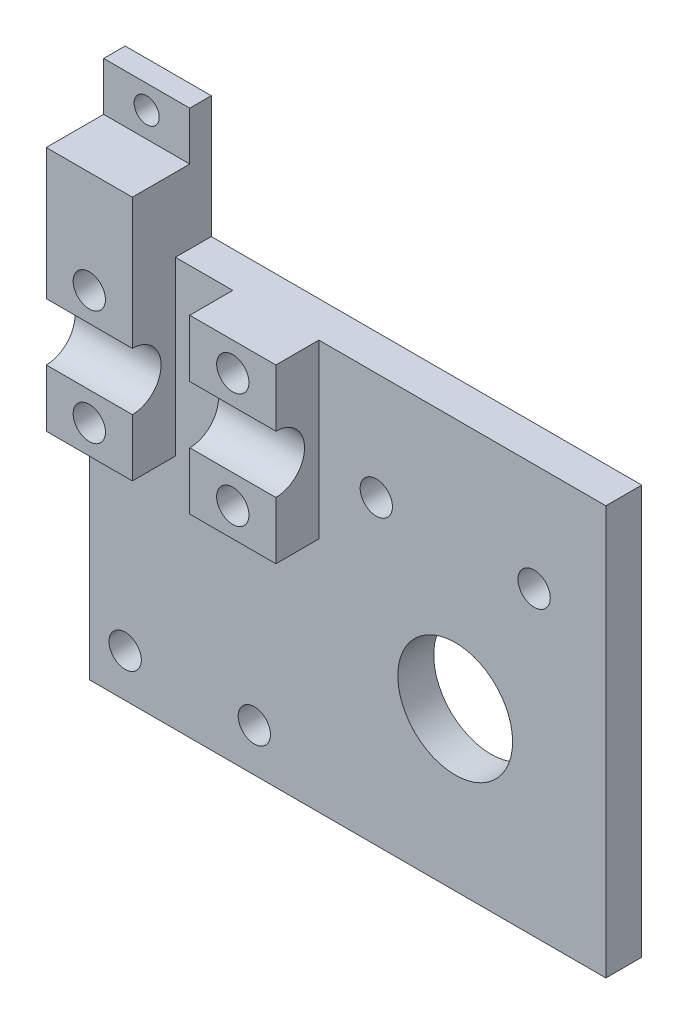
SolidWorks part; units mm, degrees
material "Printed PLA"
ref_plane "Front Plane" through (0, 0, 0) normal (0, 0, 1) x (1, 0, 0)
ref_plane "Top Plane" through (0, 0, 0) normal (0, 1, 0) x (1, 0, 0)
ref_plane "Right Plane" through (0, 0, 0) normal (1, 0, 0) x (0, 0, -1)
sketch "Sketch1" plane through (0, 0, 0) normal (0, 0, 1) x (1, 0, 0)
  line L0 (-16, 28.5) -> (56, -28.5) construction
  line L1 (-16, 28.5) -> (56, 28.5)
  line L2 (-16, 28.5) -> (-16, -28.5)
  line L3 (-16, -28.5) -> (56, -28.5)
  line L4 (56, 28.5) -> (56, -28.5)
  line L5 (20, 0) -> (0, 0) construction
  dimension "D1" = 72
  dimension "D2" = 57
  dimension "D3" = 20
extrude "Boss-Extrude1" add sketch "Sketch1" along normal blind 5
sketch "Sketch3" plane through (-16, 0, 0) normal (1, 0, 0) x (0, 0, -1)
  line L0 (-5, 28.5) -> (-11, 28.5)
  line L1 (-11, 28.5) -> (-11, 20.5)
  line L2 (-11, 12.5) -> (-11, 4.5)
  line L3 (-11, 4.5) -> (-5, 4.5)
  line L4 (-5, -28.5) -> (-5, 28.5) construction
  line L5 (-5, 4.5) -> (-5, 28.5)
  arc A0 (-11, 20.5) -> (-11, 12.5) centre (-11, 16.5) cw
  dimension "D1" = 4
  dimension "D2" = 8
  dimension "D3" = 6
extrude "Boss-Extrude2" add sketch "Sketch3" along normal blind 12
sketch "Sketch5" plane through (0, 0, 11) normal (0, 0, 1) x (1, 0, 0)
  line L0 (-10, 8.5) -> (-10, 24.5) construction
  line L1 (-10, 16.5) -> (-16, 16.5) construction
  line L2 (-16, 20.5) -> (-16, 12.5) construction
  line L3 (-10, 24.5) -> (-10, 28.5) construction
  line L4 (-4, 28.5) -> (-16, 28.5) construction
  circle A0 centre (-10, 24.5) radius 2.25
  circle A1 centre (-10, 8.5) radius 2.25
  dimension "D1" = 4.5
  dimension "D2" = 16
extrude "Cut-Extrude2" cut sketch "Sketch5" against normal through all
mirror "Mirror1" about plane through (0, 0, 0) normal (1, 0, 0) of "Cut-Extrude2", "Boss-Extrude2"
sketch "Sketch4" plane through (0, 0, 5) normal (0, 0, 1) x (1, 0, 0)
  line L0 (-16, -28.5) -> (56, -28.5) construction
  line L1 (35, -6.5) -> (35, -28.5) construction
  line L2 (19.5, -22) -> (19.5, 9) construction
  line L3 (19.5, 9) -> (50.5, 9) construction
  line L4 (50.5, 9) -> (50.5, -22) construction
  line L5 (50.5, -22) -> (19.5, -22) construction
  line L6 (19.5, -22) -> (50.5, 9) construction
  line L8 (56, -28.5) -> (56, 28.5) construction
  circle A0 centre (35, -6.5) radius 8
  circle A1 centre (19.5, 9) radius 1.75 construction
  circle A2 centre (50.5, 9) radius 1.75 construction
  circle A3 centre (50.5, -22) radius 1.75 construction
  circle A4 centre (19.5, -22) radius 1.75 construction
  dimension "D2" = 16
  dimension "D4" = 3.5
  dimension "D1" = 22
  dimension "D3" = 31
  dimension "D5" = 21
extrude "Cut-Extrude1" cut sketch "Sketch4" against normal through all
sketch "Sketch6" plane through (0, 0, 5) normal (0, 0, 1) x (1, 0, 0)
  line L0 (7, -22.5) -> (-11, -22.5) construction
  line L1 (-16, -28.5) -> (56, -28.5) construction
  line L2 (-2, -22.5) -> (-2, -17.3253) construction
  line L4 (-16, 4.5) -> (-16, -28.5) construction
  circle A0 centre (-11, -22.5) radius 2.25
  circle A1 centre (7, -22.5) radius 2.25
  dimension "D1" = 4.5
  dimension "D2" = 18
  dimension "D3" = 6
  dimension "D4" = 14
extrude "Cut-Extrude3" cut sketch "Sketch6" against normal through all
sketch "Sketch7" plane through (0, 0, 5) normal (0, 0, 1) x (1, 0, 0)
  line L0 (24, 13.5) -> (46, 13.5) construction
  line L1 (56, 28.5) -> (16, 28.5) construction
  line L2 (56, -28.5) -> (56, 28.5) construction
  circle A0 centre (46, 13.5) radius 2.25
  circle A1 centre (24, 13.5) radius 2.25
  dimension "D4" = 4.5
  dimension "D1" = 22
  dimension "D2" = 15
  dimension "D3" = 10
extrude "Cut-Extrude4" cut sketch "Sketch7" against normal through all
sketch "Sketch8" plane through (0, 0, 0) normal (0, 0, -1) x (-1, 0, 0)
  line L0 (4, 45.5) -> (16, 39) construction
  line L1 (16, 39) -> (4, 39) construction
  line L2 (16, 39) -> (16, 45.5)
  line L3 (16, 45.5) -> (4, 45.5)
  line L4 (4, 39) -> (4, 45.5)
  line L6 (16, 28.5) -> (16, -28.5) construction
  line L7 (16, 39) -> (16, 28.5)
  line L8 (-56, 28.5) -> (16, 28.5) construction
  line L9 (16, 28.5) -> (4, 28.5)
  line L10 (4, 28.5) -> (4, 39)
  circle A0 centre (10, 42.25) radius 1.75
  dimension "D1" = 3.5
  dimension "D4" = 6
  dimension "D2" = 6.5
  dimension "D3" = 12
  dimension "D5" = 17
extrude "Boss-Extrude3" add sketch "Sketch8" against normal blind 3
sketch "Sketch9" plane through (0, 0, 3) normal (0, 0, 1) x (1, 0, 0)
  line L0 (-16, 28.5) -> (-16, 45.5) construction
  line L1 (-16, 38.75) -> (-4, 38.75)
  line L2 (-16, 38.75) -> (-16, 28.5)
  line L3 (-16, 28.5) -> (-4, 28.5)
  line L4 (-4, 38.75) -> (-4, 28.5)
  circle A0 centre (-10, 42.25) radius 1.75 construction
  dimension "D1" = 3.5
extrude "Boss-Extrude4" add sketch "Sketch9" along normal blind 8
